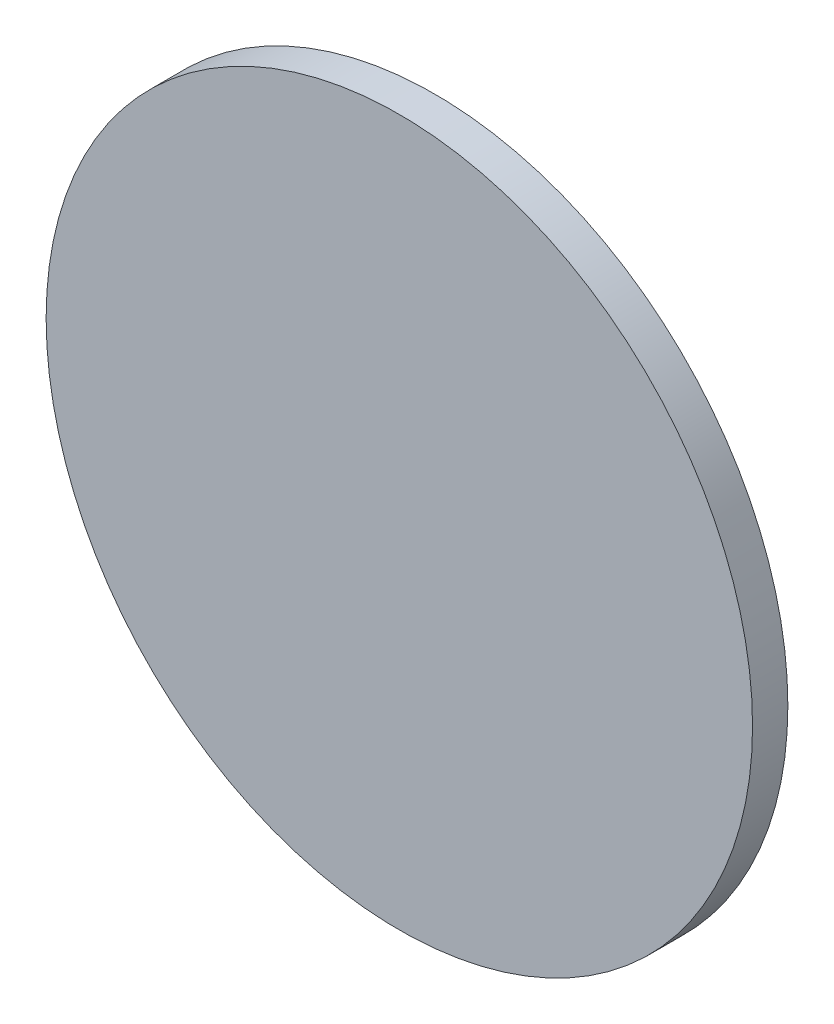
SolidWorks part; units mm, degrees
ref_plane "Front Plane" through (0, 0, 0) normal (0, 0, 1) x (1, 0, 0)
ref_plane "Top Plane" through (0, 0, 0) normal (0, 1, 0) x (1, 0, 0)
ref_plane "Right Plane" through (0, 0, 0) normal (1, 0, 0) x (0, 0, -1)
sketch "Sketch1" plane through (0, 0, 0) normal (0, 0, 1) x (1, 0, 0)
  circle A0 centre (0, 0) radius 40
  dimension "D1" = 80
extrude "Boss-Extrude1" add sketch "Sketch1" along normal blind 4 contours A0
